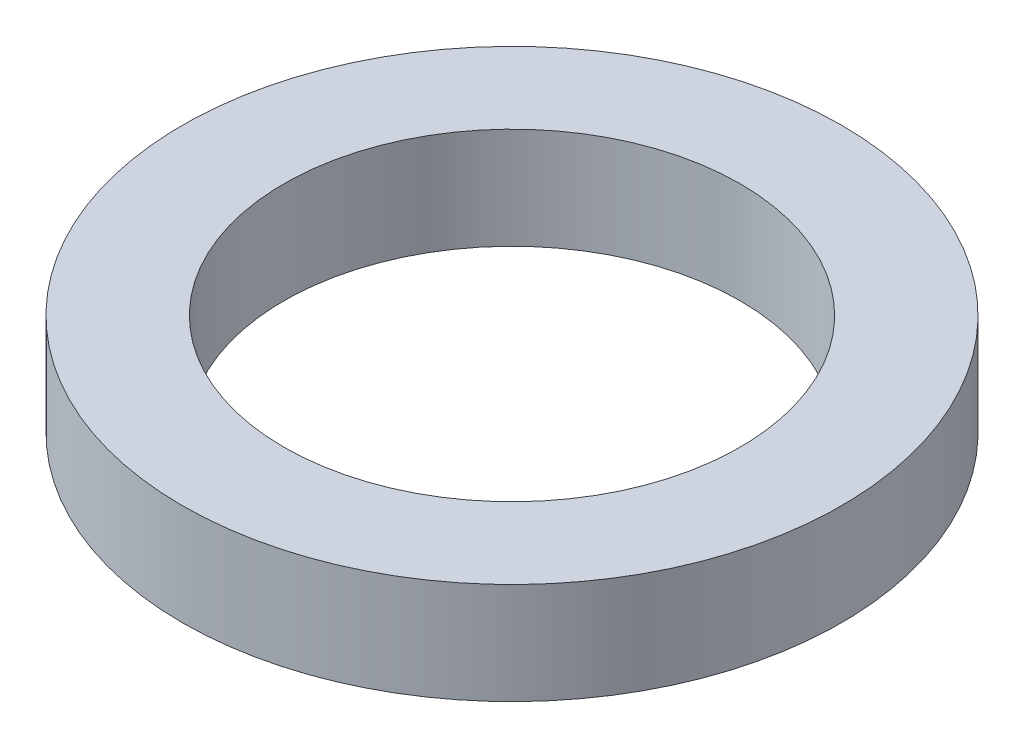
SolidWorks part; units mm, degrees
ref_plane "Plan de face" through (0, 0, 0) normal (0, 0, 1) x (1, 0, 0)
ref_plane "Plan de dessus" through (0, 0, 0) normal (0, 1, 0) x (1, 0, 0)
ref_plane "Plan de droite" through (0, 0, 0) normal (1, 0, 0) x (0, 0, -1)
sketch "Sketch1" plane through (0, 0, 0) normal (0, 1, 0) x (1, 0, 0)
  circle A0 centre (0, 0) radius 2.25
  circle A1 centre (0, 0) radius 3.25
  dimension "D1" = 4.5
  dimension "D2" = 6.5
extrude "Boss-Extrude1" add sketch "Sketch1" along normal blind 1
